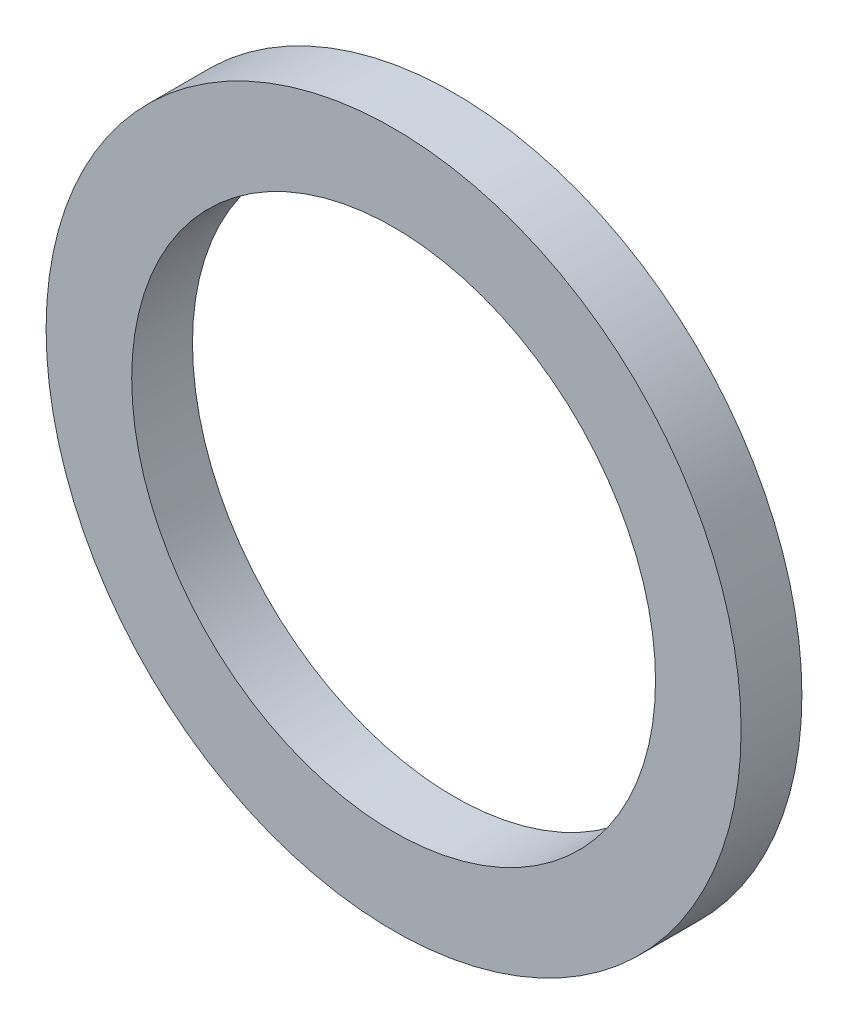
SolidWorks part; units mm, degrees
ref_plane "Ön Düzlem" through (0, 0, 0) normal (0, 0, 1) x (1, 0, 0)
ref_plane "Üst Düzlem" through (0, 0, 0) normal (0, 1, 0) x (1, 0, 0)
ref_plane "Sağ Düzlem" through (0, 0, 0) normal (1, 0, 0) x (0, 0, -1)
sketch "Çizim1" plane through (0, 0, 0) normal (0, 0, 1) x (1, 0, 0)
  circle A0 centre (0, 0) radius 14.29
  circle A1 centre (0, 0) radius 11.6
  circle A2 centre (0, 0) radius 10.77
  dimension "D1" = 28.58
  dimension "D2" = 23.2
  dimension "D3" = 21.54
extrude "Yükseklik-Ekstrüzyon4" add sketch "Çizim1" along normal blind 2.5 contours A1 A2 | A0 A1
